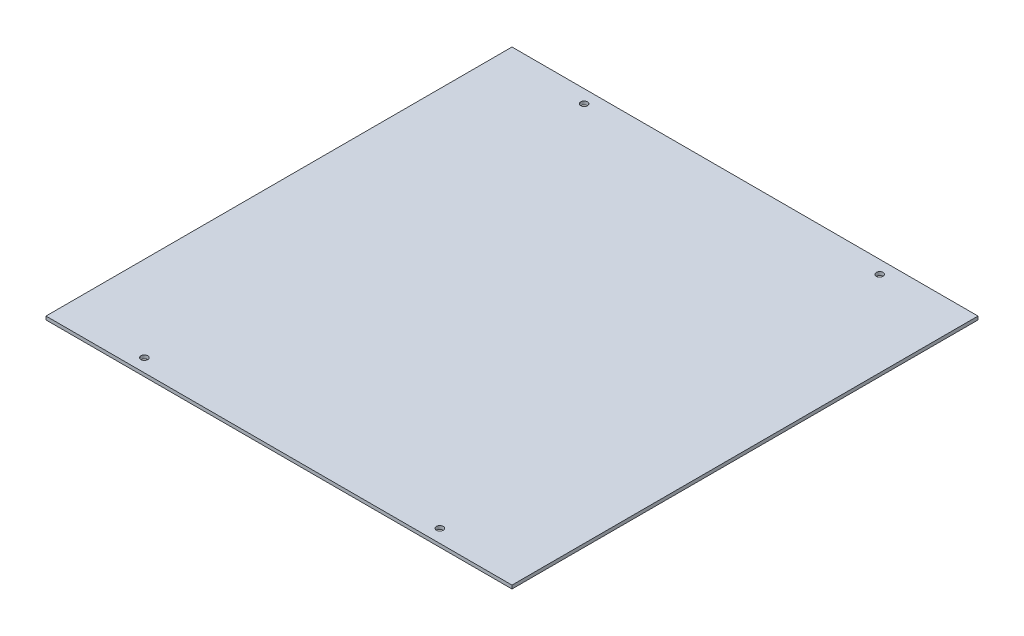
SolidWorks part; units mm, degrees
ref_plane "Alzado" through (0, 0, 0) normal (0, 0, 1) x (1, 0, 0)
ref_plane "Planta" through (0, 0, 0) normal (0, 1, 0) x (1, 0, 0)
ref_plane "Vista lateral" through (0, 0, 0) normal (1, 0, 0) x (0, 0, -1)
sketch "Croquis1" plane through (0, 0, 0) normal (0, 1, 0) x (1, 0, 0)
  line L0 (0, 0) -> (0, 64.6411) construction
  line L1 (-205, 205) -> (205, 205)
  line L2 (-205, 205) -> (-205, -205)
  line L3 (-205, -205) -> (205, -205)
  line L4 (205, 205) -> (205, -205)
  line L5 (-205, 205) -> (205, -205) construction
  line L6 (-205, -205) -> (205, 205) construction
  line L7 (0, 64.6411) -> (0, 0) construction
  line L8 (0, 0) -> (-69.8111, 0) construction
  circle A0 centre (-130, 193.4893) radius 3
  circle A1 centre (130, 193.4893) radius 3
  circle A2 centre (130, -193.4893) radius 3
  circle A3 centre (-130, -193.4893) radius 3
  point P0 (0, 0)
  dimension "D4" = 6
  dimension "D1" = 410
  dimension "D2" = 410
  dimension "D3" = 11.5107
  dimension "D5" = 130
extrude "Saliente-Extruir1" add sketch "Croquis1" along normal blind 3
